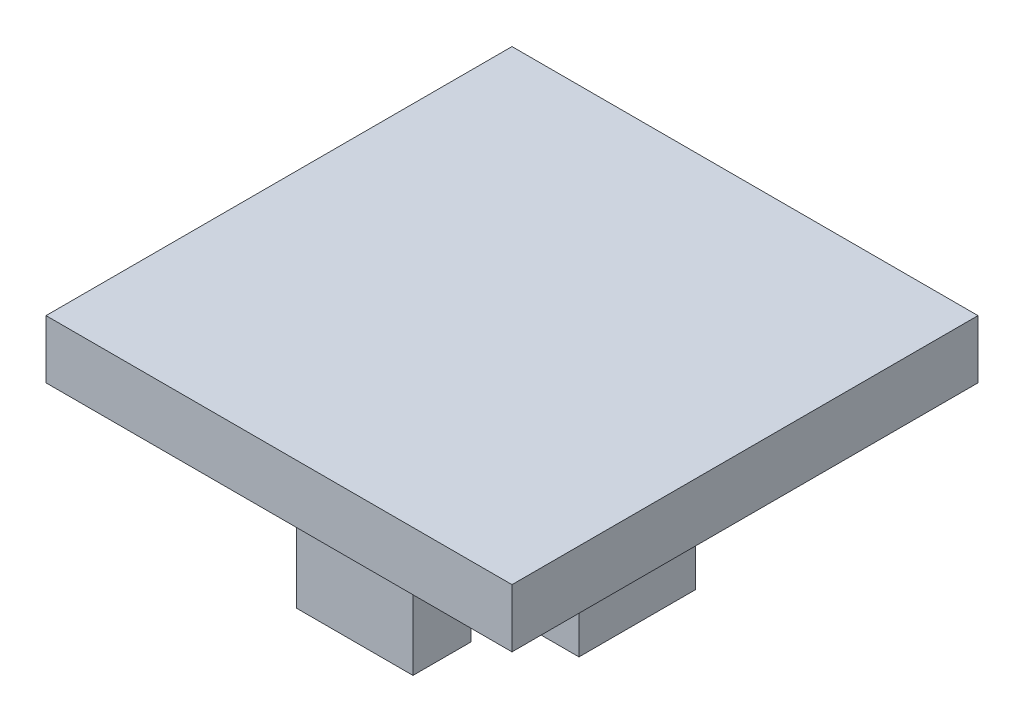
SolidWorks part; units mm, degrees
ref_plane "Front Plane" through (0, 0, 0) normal (0, 0, 1) x (1, 0, 0)
ref_plane "Top Plane" through (0, 0, 0) normal (0, 1, 0) x (1, 0, 0)
ref_plane "Right Plane" through (0, 0, 0) normal (1, 0, 0) x (0, 0, -1)
sketch "Sketch1" plane through (0, 0, 0) normal (0, 1, 0) x (1, 0, 0)
  line L1 (-4, -4) -> (4, -4)
  line L2 (-4, -4) -> (-4, 4)
  line L3 (-4, 4) -> (4, 4)
  line L4 (4, -4) -> (4, 4)
  line L5 (-4, -4) -> (4, 4) construction
  line L6 (-4, 4) -> (4, -4) construction
  point P0 (0, 0)
  dimension "D1" = 8
  dimension "D2" = 8
extrude "Boss-Extrude1" add sketch "Sketch1" along normal blind 1
sketch "Sketch2" plane through (0, 0, 0) normal (0, -1, 0) x (1, 0, 0)
  line L23 (-1, 1.7) -> (1, 1.7)
  line L24 (-1, 1.7) -> (-1, 2.7)
  line L25 (-1, 2.7) -> (1, 2.7)
  line L26 (1, 1.7) -> (1, 2.7)
  line L27 (-1, 1.7) -> (1, 2.7) construction
  line L28 (-1, 2.7) -> (1, 1.7) construction
  line L29 (1.15, 1) -> (2.15, 1)
  line L30 (1.15, 1) -> (1.15, -1)
  line L31 (1.15, -1) -> (2.15, -1)
  line L32 (2.15, 1) -> (2.15, -1)
  line L33 (1.15, 1) -> (2.15, -1) construction
  line L34 (1.15, -1) -> (2.15, 1) construction
  point P0 (0, 2)
  point P5 (0, 2.2)
  point P10 (1.65, 0)
  point P20 (0, 0)
  point P22 (0, 0)
  dimension "D1" = 1.7
  dimension "D2" = 1
  dimension "D3" = 2
  dimension "D4" = 1.15
  dimension "D5" = 1
  dimension "D6" = 2
extrude "Boss-Extrude2" add sketch "Sketch2" along normal blind 2.5
sketch "Sketch3" plane through (0, 0, 1.7) normal (0, 0, -1) x (-1, 0, 0)
  line L0 (1, -2.5) -> (1, 0) construction
  line L1 (1, -2) -> (-1, -2)
  line L2 (1, -2) -> (1, -1.5)
  line L3 (1, -1.5) -> (-1, -1.5)
  line L4 (-1, -2) -> (-1, -1.5)
  line L5 (-1, -2.5) -> (-1, 0) construction
  line L6 (1, -2.5) -> (-1, -2.5) construction
  point P10 (0, 0)
  dimension "D1" = 0.5
  dimension "D2" = 0.5
extrude "Boss-Extrude3" add sketch "Sketch3" along normal blind 0.5
chamfer "Chamfer2" distance 0.3 angle 45 1 edges at (0, -2, 1.2)
mirror "Mirror1" about plane through (0, 0, 0) normal (1, 0, 0) of "Boss-Extrude2"
mirror "Mirror2" about plane through (0, 0, 0) normal (0, 0, 1) of "Boss-Extrude2", "Boss-Extrude3", "Chamfer2"
fillet "Fillet1" radius 1 4 edges at (0, 0, 2.7) (-2.15, 0, 0) (2.15, 0, 0) (0, 0, -2.7)
